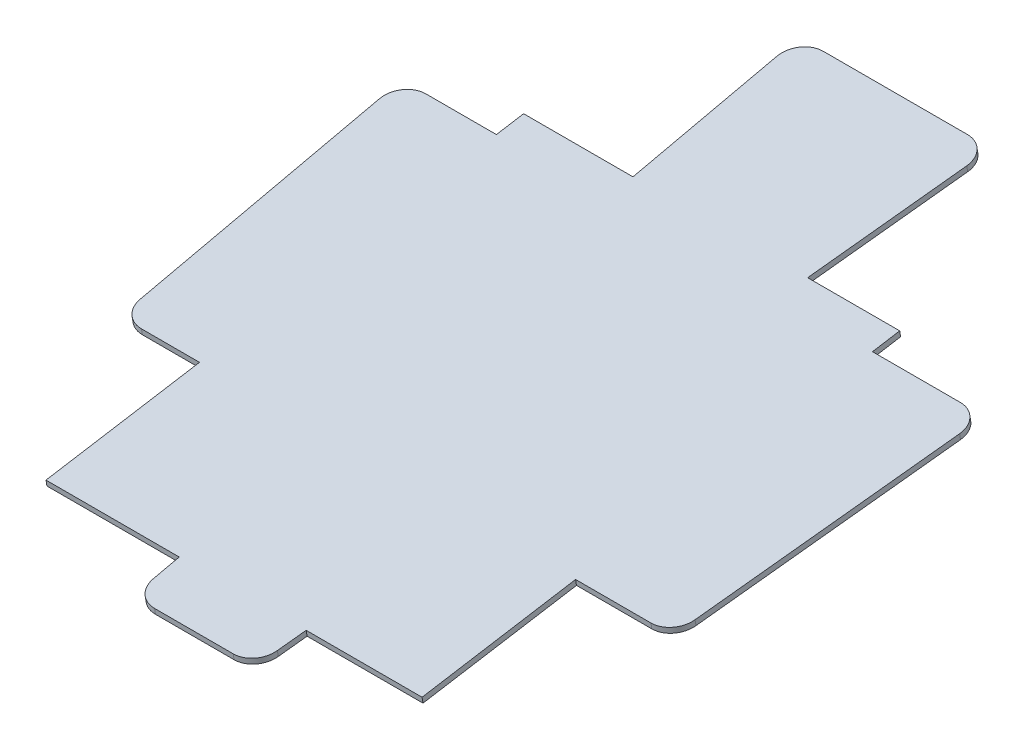
SolidWorks part; units mm, degrees
ref_plane "Front Plane" through (0, 0, 0) normal (0, 0, 1) x (1, 0, 0)
ref_plane "Top Plane" through (0, 0, 0) normal (0, 1, 0) x (1, 0, 0)
ref_plane "Right Plane" through (0, 0, 0) normal (1, 0, 0) x (0, 0, -1)
sketch "Sketch2" plane through (0, 631.8821, 103.8482) normal (0, 0.9868, 0.1622) x (1, 0, 0)
  line L0 (100, -1224.0672) -> (100, -1137.3475) construction
  line L1 (-100, -1224.0672) -> (100, -1224.0672) construction
  line L3 (100, -954.2422) -> (100, -969.611) construction
  line L4 (-100, -954.2422) -> (100, -954.2422) construction
  line L6 (154.0945, -1137.3475) -> (162.3703, -969.611) construction
  line L7 (154.0945, -1137.3475) -> (-154.0945, -1137.3475) construction
  line L8 (-154.0945, -1137.3475) -> (-162.3703, -969.611) construction
  line L9 (162.3703, -969.611) -> (-162.3703, -969.611) construction
  line L10 (100, -1224.0672) -> (100, -1137.3475)
  line L11 (-100, -1224.0672) -> (-35.3768, -1224.0672)
  line L13 (100, -954.2422) -> (100, -969.611)
  line L14 (-100, -954.2422) -> (-48.6895, -954.2422)
  line L16 (154.0945, -1137.3475) -> (162.3703, -969.611)
  line L17 (154.0945, -1137.3475) -> (100, -1137.3475)
  line L18 (-154.0945, -1137.3475) -> (-162.3703, -969.611)
  line L19 (162.3703, -969.611) -> (100, -969.611)
  line L20 (-109.652, -969.611) -> (-162.3703, -969.611)
  line L21 (-109.652, -1137.3475) -> (-154.0945, -1137.3475)
  line L22 (53.5706, -855.311) -> (-53.5706, -855.311) construction
  line L23 (53.5706, -855.311) -> (47.9312, -969.611) construction
  line L24 (53.5706, -855.311) -> (-53.5706, -855.311)
  line L25 (53.5706, -855.311) -> (48.6895, -954.2422)
  line L26 (-109.652, -1224.0672) -> (-109.652, -1137.3475) construction
  line L27 (-53.5706, -855.311) -> (-48.6895, -954.2422)
  line L28 (48.6895, -954.2422) -> (100, -954.2422)
  line L29 (0, -37.0742) -> (0, 37.0742) construction
  line L30 (35.3768, -1224.0672) -> (34.0161, -1251.6475) construction
  line L31 (34.0161, -1251.6475) -> (0, -1251.6475) construction
  line L32 (35.3768, -1224.0672) -> (34.0161, -1251.6475)
  line L33 (34.0161, -1251.6475) -> (-34.0161, -1251.6475)
  line L34 (-35.3768, -1224.0672) -> (-34.0161, -1251.6475)
  line L35 (35.3768, -1224.0672) -> (100, -1224.0672)
  line L36 (-100, -1224.0672) -> (-109.652, -1224.0672) construction
  line L37 (-109.652, -1224.0672) -> (-109.652, -1137.3475)
  line L38 (-100, -1224.0672) -> (-109.652, -1224.0672)
  line L39 (-109.652, -954.2422) -> (-109.652, -969.611) construction
  line L40 (-100, -954.2422) -> (-109.652, -954.2422) construction
  line L41 (-109.652, -954.2422) -> (-109.652, -969.611)
  line L42 (-100, -954.2422) -> (-109.652, -954.2422)
  point P18 (0, -855.311)
extrude "Boss-Extrude1" add sketch "Sketch2" against normal up to vertex (3.175 mm away) from vertex at 0
fillet "Fillet1" radius 12.7 8 edges at (-154.0945, 445.8698, 1225.8826) (-162.3703, 473.0719, 1060.3666) (-53.5706, 491.6082, 947.5796) (53.5706, 491.6082, 947.5796) (162.3703, 473.0719, 1060.3666) (154.0945, 445.8698, 1225.8826) (34.0161, 427.3335, 1338.6696) (-34.0161, 427.3335, 1338.6696)
